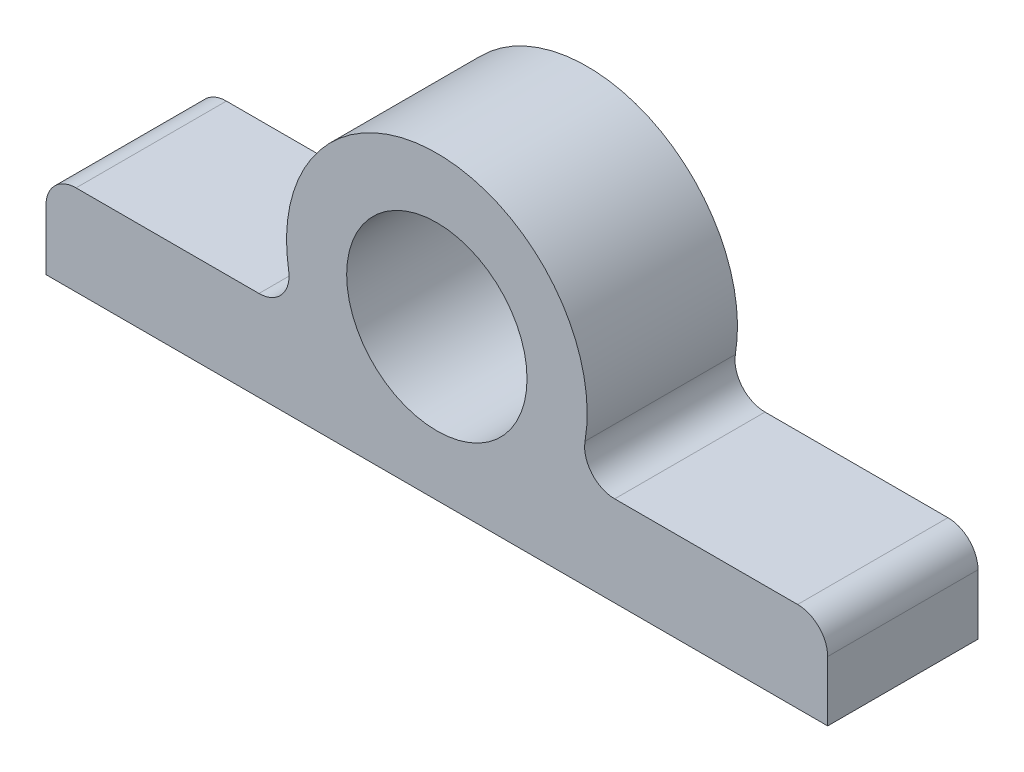
SolidWorks part; units mm, degrees
ref_plane "Front Plane" through (0, 0, 0) normal (0, 0, 1) x (1, 0, 0)
ref_plane "Top Plane" through (0, 0, 0) normal (0, 1, 0) x (1, 0, 0)
ref_plane "Right Plane" through (0, 0, 0) normal (1, 0, 0) x (0, 0, -1)
sketch "Sketch1" plane through (0, 0, 0) normal (0, 0, 1) x (1, 0, 0)
  line L0 (-65, -25) -> (-65, -15)
  line L1 (-60, -10) -> (-29.5804, -10)
  line L2 (-65, -25) -> (65, -25)
  line L3 (65, -25) -> (65, -15)
  line L4 (60, -10) -> (29.5804, -10)
  circle A0 centre (0, 0) radius 15
  arc A1 (24.6503, -4.1667) -> (-24.6503, -4.1667) centre (0, 0) ccw
  arc A2 (29.5804, -10) -> (24.6503, -4.1667) centre (29.5804, -5) cw
  arc A3 (-29.5804, -10) -> (-24.6503, -4.1667) centre (-29.5804, -5) ccw
  arc A4 (65, -15) -> (60, -10) centre (60, -15) ccw
  arc A5 (-65, -15) -> (-60, -10) centre (-60, -15) cw
  point P15 (65, -10)
  point P18 (-65, -10)
  dimension "D1" = 30
  dimension "D2" = 50
  dimension "D7" = 5
  dimension "D8" = 5
  dimension "D3" = 25
  dimension "D4" = 130
  dimension "D5" = 15
  dimension "D6" = 15
extrude "Boss-Extrude1" add sketch "Sketch1" along normal blind 25
